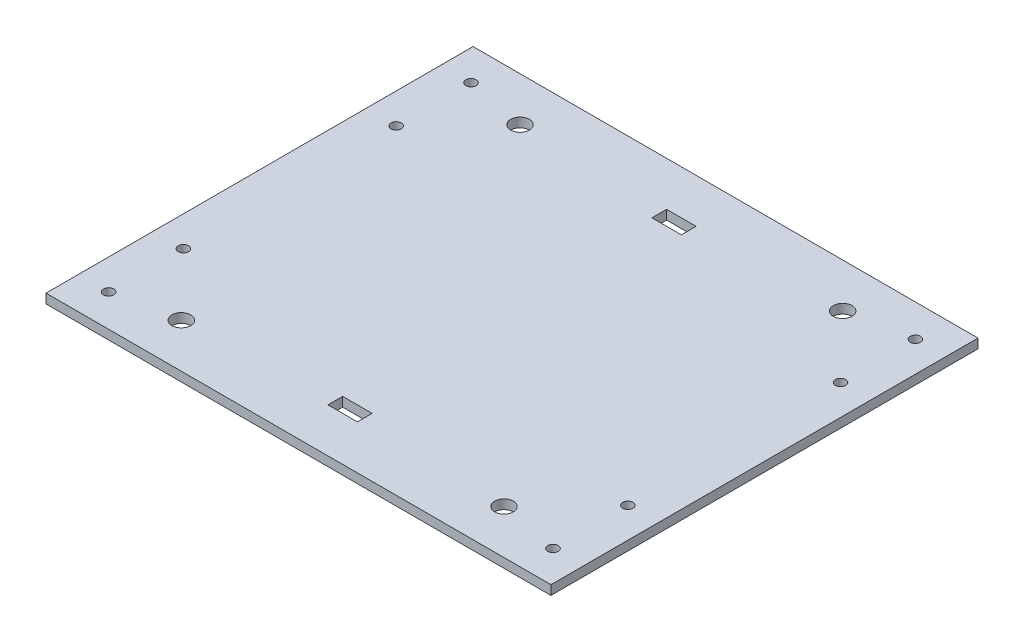
SolidWorks part; units mm, degrees
material "Acrylic (Medium-high impact)"
ref_plane "Front Plane" through (0, 0, 0) normal (0, 0, 1) x (1, 0, 0)
ref_plane "Top Plane" through (0, 0, 0) normal (0, 1, 0) x (1, 0, 0)
ref_plane "Right Plane" through (0, 0, 0) normal (1, 0, 0) x (0, 0, -1)
sketch "Sketch1" plane through (0, 0, 0) normal (0, 1, 0) x (1, 0, 0)
  line L0 (69.775, 145) -> (69.775, 0) construction
  line L1 (0, 0) -> (139.55, 0)
  line L3 (0, 145) -> (139.55, 145)
  line L5 (0, 72.5) -> (139.55, 72.5) construction
  line L6 (64.775, 130) -> (74.775, 130)
  line L7 (64.775, 130) -> (64.775, 125)
  line L8 (64.775, 125) -> (74.775, 125)
  line L9 (74.775, 130) -> (74.775, 125)
  line L10 (64.775, 15) -> (64.775, 20)
  line L11 (64.775, 20) -> (74.775, 20)
  line L12 (74.775, 15) -> (74.775, 20)
  line L13 (64.775, 15) -> (74.775, 15)
  line L15 (0, 145) -> (-15.95, 145)
  line L17 (0, 0) -> (-15.95, 0)
  line L18 (-15.95, 145) -> (-15.95, 0)
  line L19 (139.55, 145) -> (155.5, 145)
  line L21 (139.55, 0) -> (155.5, 0)
  line L22 (155.5, 145) -> (155.5, 0)
  circle A0 centre (15, 130) radius 3.175
  circle A1 centre (124.55, 130) radius 3.175
  circle A2 centre (15, 15) radius 3.175
  circle A3 centre (124.55, 15) radius 3.175
  circle A6 centre (-5.663, 134.0145) radius 1.75
  circle A7 centre (-5.663, 108.6145) radius 1.75
  circle A8 centre (145.213, 134.0145) radius 1.75
  circle A9 centre (145.213, 108.6145) radius 1.75
  circle A10 centre (145.213, 10.9855) radius 1.75
  circle A11 centre (-5.663, 10.9855) radius 1.75
  circle A12 centre (145.213, 36.3855) radius 1.75
  circle A13 centre (-5.663, 36.3855) radius 1.75
  point P11 (69.775, 130)
  point P14 (64.775, 127.5)
  point P15 (64.775, 17.5)
  point P36 (0, 0)
  point P37 (0, 0)
  point P38 (0, 0)
  dimension "D7" = 6.35
  dimension "D9" = 3.5
  dimension "D13" = 3.5
  dimension "D15" = 10.287
  dimension "D1" = 139.55
  dimension "D2" = 145
  dimension "D3" = 15
  dimension "D4" = 10
  dimension "D5" = 5
  dimension "D6" = 0
  dimension "D8" = 15
  dimension "D10" = 15.95
  dimension "D11" = 15.95
  dimension "D12" = 10.9855
  dimension "D14" = 25.4
extrude "Boss-Extrude2" add sketch "Sketch1" along normal blind 3.175 contours L3 L19 L22 L21 L1 L17 L18 L15 | L6 L9 L8 L7 | A1 | A3 | L13 L12 L11 L10 | A2 | A0 | A7 | A6 | A11 | A13 | A10 | A12 | A9 | A8
